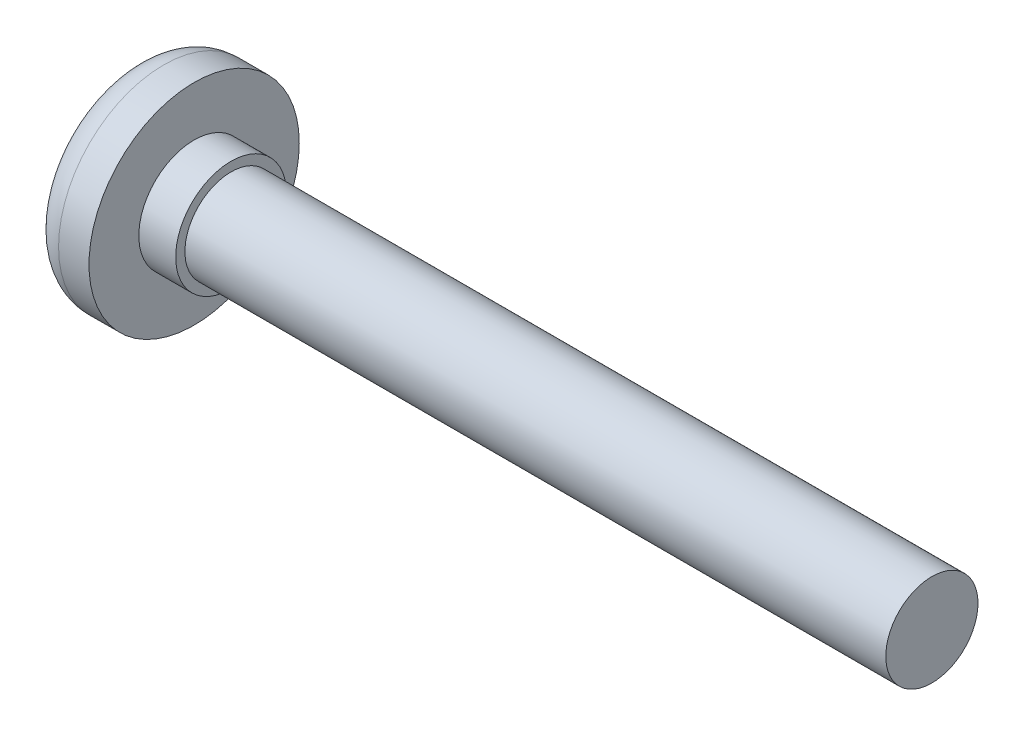
SolidWorks part; units mm, degrees
ref_plane "Front Plane" through (0, 0, 0) normal (0, 0, 1) x (1, 0, 0)
ref_plane "Top Plane" through (0, 0, 0) normal (0, 1, 0) x (1, 0, 0)
ref_plane "Right Plane" through (0, 0, 0) normal (1, 0, 0) x (0, 0, -1)
sketch "Sketch1" plane through (0, 0, 0) normal (0, 0, 1) x (1, 0, 0)
  line L0 (22.7734, 0) -> (-45.9293, 0) construction
  line L1 (-20, 2.85) -> (-21.65, 2.85)
  line L2 (-21.65, 2.85) -> (-21.65, 0)
  line L3 (0, 1.5) -> (-20, 1.5)
  line L4 (-20, 1.5) -> (-20, 2.85)
  line L5 (-21.65, 0) -> (0, 0)
  line L6 (0, 0) -> (0, 1.5)
  dimension "d2" = 5.7
  dimension "d1" = 3
  dimension "k" = 1.65
  dimension "L" = 20
revolve "Revolve1" add sketch "Sketch1" angle 360 about L0
cosmetic thread "Cosmetic Thread1" parameters "D2"=7.5
sketch "Sketch2" plane through (-21.65, 0, 0) normal (-1, 0, 0) x (0, 0, 1)
  line L1 (0.7, -1.2124) -> (1.4, 0)
  line L2 (1.4, 0) -> (0.7, 1.2124)
  line L3 (0.7, 1.2124) -> (-0.7, 1.2124)
  line L4 (-0.7, 1.2124) -> (-1.4, 0)
  line L5 (-1.4, 0) -> (-0.7, -1.2124)
  line L6 (-0.7, -1.2124) -> (0.7, -1.2124)
  circle A0 centre (0, 0) radius 1.4 construction
  arc A1 (-0.7, 1.2124) -> (0.7, 1.2124) centre (0, 1.7824) ccw
  arc A2 (0.7, 1.2124) -> (1.4, 0) centre (1.5436, 0.8912) ccw
  arc A3 (1.4, 0) -> (0.7, -1.2124) centre (1.5436, -0.8912) ccw
  arc A4 (0.7, -1.2124) -> (-0.7, -1.2124) centre (0, -1.7824) ccw
  arc A5 (-0.7, -1.2124) -> (-1.4, 0) centre (-1.5436, -0.8912) ccw
  arc A6 (-1.4, 0) -> (-0.7, 1.2124) centre (-1.5436, 0.8912) ccw
  dimension "apu1" = 0.57
  dimension "A" = 2.8
extrude "Extrude1" cut sketch "Sketch2" against normal blind 1 contours A6 A5 A4 A3 A2 A1
fillet "Fillet1" radius 0.825 1 edges at (-21.65, 0, -2.85)
fillet "Fillet2" radius 0.1629 6 edges at (-21.15, 0, 1.4) (-21.15, -1.2124, 0.7) (-21.15, -1.2124, -0.7) (-21.15, 0, -1.4) (-21.15, 1.2124, -0.7) (-21.15, 1.2124, 0.7)
sketch "Sketch3" plane through (0, 0, 0) normal (1, 0, 0) x (0, 0, -1)
  circle A0 centre (0, 0) radius 1.25
  dimension "apu4" = 2.5
extrude "Sisäkierre" cut sketch "Sketch3" against normal blind 19 flip side to cut
equation "\"D1@Fillet1\" = \"k@Sketch1\" / 2"
equation "\"apu3@Fillet2\" =\"d2@Sketch1\" / 35"
equation "\"apu2@Sisäkierre\" =  ( 9.5 / 10 )  * \"L@Sketch1\""
equation "\"apu1@Sketch2\" = \"d2@Sketch1\" / 10"
